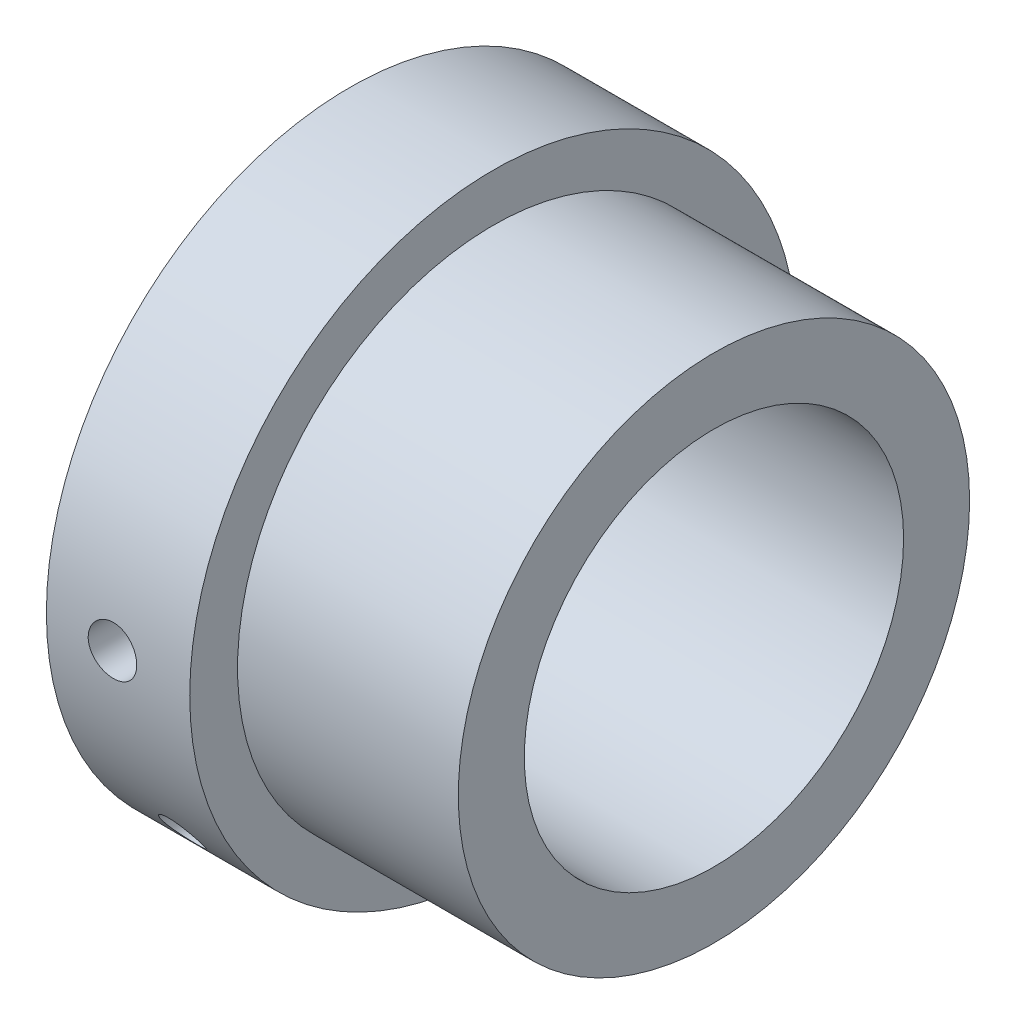
SolidWorks part; units mm, degrees
ref_plane "Front Plane" through (0, 0, 0) normal (0, 0, 1) x (1, 0, 0)
ref_plane "Top Plane" through (0, 0, 0) normal (0, 1, 0) x (1, 0, 0)
ref_plane "Right Plane" through (0, 0, 0) normal (1, 0, 0) x (0, 0, -1)
sketch "Sketch1" plane through (0, 0, 0) normal (1, 0, 0) x (0, 0, -1)
  circle A0 centre (0, 0) radius 6.35
  circle A1 centre (0, 0) radius 3.9688
  dimension "D1" = 7.9375
  dimension "D2" = 12.7
extrude "Boss-Extrude1" add sketch "Sketch1" along normal blind 7.62
sketch "Sketch2" plane through (0, 0, 0) normal (0, 0, 1) x (1, 0, 0)
  line L0 (7.62, 6.35) -> (0, 6.35) construction
  line L1 (3, 6.35) -> (7.62, 6.35)
  line L2 (3, 6.35) -> (3, 5.35)
  line L3 (3, 5.35) -> (7.62, 5.35)
  line L4 (7.62, 6.35) -> (7.62, 5.35)
  line L5 (0, 6.35) -> (0, -6.35) construction
  line L7 (7.62, -6.35) -> (7.62, 6.35) construction
  dimension "D1" = 3
  dimension "D2" = 0
  dimension "D3" = 1
ref_axis "Axis1" through (7.62, 0, 0) along (-1, 0, 0)
revolve "Cut-Revolve1" cut sketch "Sketch2" angle 360 about axis through (7.62, 0, 0) along (-1, 0, 0)
hole_wizard "#60 (0.04) Diameter Hole1" positions "Sketch4" profile "Sketch3" hole size "#60" standard "ANSI Inch"
sketch "Sketch4" plane through (0, 0, 0) normal (0, 0, 1) x (1, 0, 0)
  line L0 (7.62, 0) -> (0, 0) construction
  point P0 (1.3829, 0)
sketch "Sketch3" plane through (1.3829, 0, 0) normal (1, 0, 0) x (0, 1, 0)
  line L0 (0, 0) -> (0, 25.7052)
  line L1 (0, 25.7052) -> (0.508, 25.4)
  line L2 (0.508, 25.4) -> (0.508, 0)
  line L5 (0.508, 0) -> (0, 0)
  line L10 (0, 25.7052) -> (-0.508, 25.4) construction
  line L11 (0, -6.35) -> (0, 107.95) construction
  dimension "Hole Dia." = 1.016
  dimension "Hole Depth" = 25.4
  dimension "Drill Angle" = 118
ref_plane "Plane1" through (0, 0, -5.08) normal (0, 0, 1) x (1, 0, 0)
hole_wizard "1/32 (0.03125) Diameter Hole1" positions "Sketch6" profile "Sketch5" hole size "1/32" standard "ANSI Inch"
sketch "Sketch6" plane through (0, 0, -5.08) normal (0, 0, 1) x (1, 0, 0)
  line L1 (0, 6.35) -> (0, -6.35) construction
  point P0 (1.524, -3.8659)
  dimension "D1" = 1.524
sketch "Sketch5" plane through (1.524, -3.8659, -5.08) normal (1, 0, 0) x (0, 1, 0)
  line L0 (0, 0) -> (0, 70.3425)
  line L1 (0, 70.3425) -> (0.3969, 70.104)
  line L2 (0.3969, 70.104) -> (0.3969, 0)
  line L5 (0.3969, 0) -> (0, 0)
  line L10 (0, 70.3425) -> (-0.3969, 70.104) construction
  line L11 (0, -6.35) -> (0, 107.95) construction
  dimension "Hole Dia." = 0.7937
  dimension "Hole Depth" = 70.104
  dimension "Drill Angle" = 118
